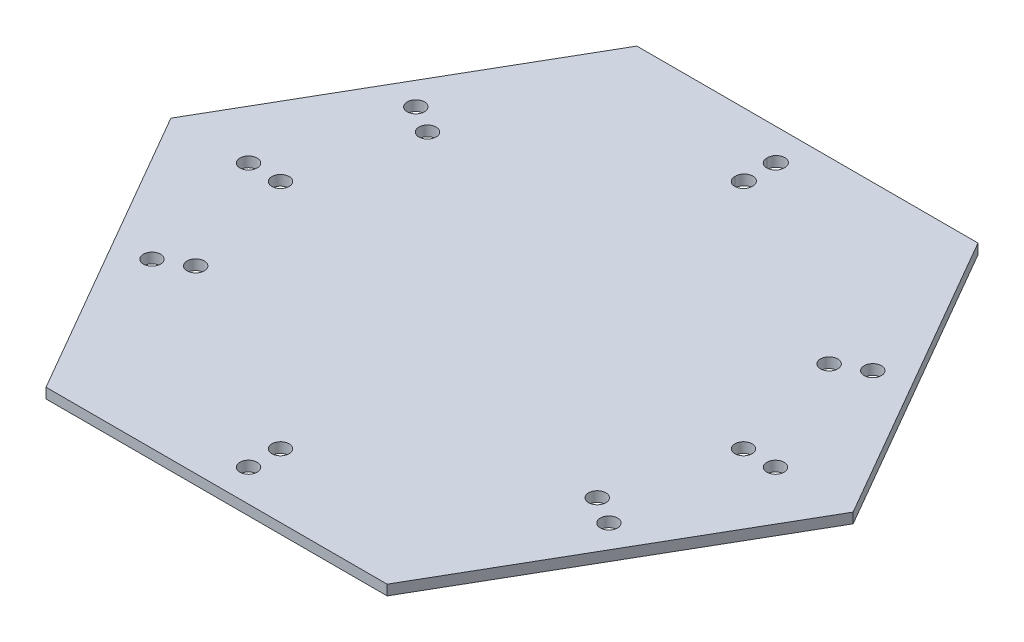
SolidWorks part; units mm, degrees
material "6063-T6"
ref_plane "Front Plane" through (0, 0, 0) normal (0, 0, 1) x (1, 0, 0)
ref_plane "Top Plane" through (0, 0, 0) normal (0, 1, 0) x (1, 0, 0)
ref_plane "Right Plane" through (0, 0, 0) normal (1, 0, 0) x (0, 0, -1)
sketch "Sketch1" plane through (0, 0, 0) normal (0, 1, 0) x (1, 0, 0)
  line L1 (160, 0) -> (80, 138.5641)
  line L2 (80, 138.5641) -> (-80, 138.5641)
  line L3 (-80, 138.5641) -> (-160, 0)
  line L4 (-160, 0) -> (-80, -138.5641)
  line L5 (-80, -138.5641) -> (80, -138.5641)
  line L6 (80, -138.5641) -> (160, 0)
  circle A0 centre (0, 0) radius 160 construction
  dimension "D1" = 320
extrude "Boss-Extrude1" add sketch "Sketch1" along normal blind 4.78
sketch "Sketch2" plane through (0, 4.78, 0) normal (0, 1, 0) x (1, 0, 0)
  line L0 (-80, -138.5641) -> (80, -138.5641) construction
  circle A0 centre (0, -123.5641) radius 4.05
  circle A1 centre (0, -108.5641) radius 4.05
  dimension "D1" = 8.1
  dimension "D2" = 8.1
  dimension "D3" = 15
  dimension "D4" = 15
extrude "Cut-Extrude1" cut sketch "Sketch2" against normal up to surface (4.78 mm away) up to face at (0, 0, 0)
pattern_circular "CirPattern1" count 6 over 360 about axis through (0, 0, -0.1801) along (0, 1, 0) of "Cut-Extrude1"
pattern_circular "CirPattern2" count 4 over 360 about axis through (0, 0, 0.0017) along (0, 1, 0) of "Cut-Extrude1"
